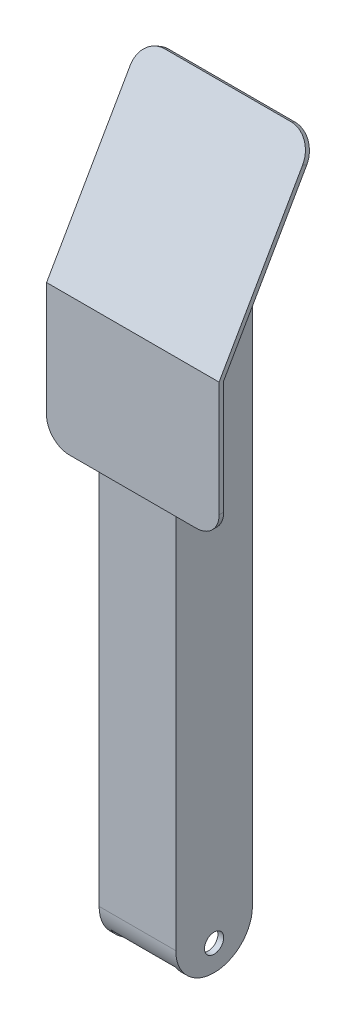
SolidWorks part; units mm, degrees
ref_plane "Front Plane" through (0, 0, 0) normal (0, 0, 1) x (1, 0, 0)
ref_plane "Top Plane" through (0, 0, 0) normal (0, 1, 0) x (1, 0, 0)
ref_plane "Right Plane" through (0, 0, 0) normal (1, 0, 0) x (0, 0, -1)
sketch "Sketch1" plane through (0, 0, 0) normal (0, 1, 0) x (1, 0, 0)
  line L1 (-10.795, -10.795) -> (10.795, -10.795)
  line L2 (-10.795, -10.795) -> (-10.795, 10.795)
  line L3 (-10.795, 10.795) -> (10.795, 10.795)
  line L4 (10.795, -10.795) -> (10.795, 10.795)
  line L5 (-10.795, -10.795) -> (10.795, 10.795) construction
  line L6 (-10.795, 10.795) -> (10.795, -10.795) construction
  line L7 (-12.7, -12.7) -> (12.7, -12.7)
  line L8 (-12.7, -12.7) -> (-12.7, 12.7)
  line L9 (-12.7, 12.7) -> (12.7, 12.7)
  line L10 (12.7, -12.7) -> (12.7, 12.7)
  line L11 (-12.7, -12.7) -> (12.7, 12.7) construction
  line L12 (-12.7, 12.7) -> (12.7, -12.7) construction
  point P0 (0, 0)
  point P6 (0, 0)
  dimension "D1" = 1.905
  dimension "D2" = 25.4
extrude "Boss-Extrude1" add sketch "Sketch1" along normal blind 228.6
sketch "Sketch2" plane through (0, 0, 0) normal (1, 0, 0) x (0, 0, -1)
  line L0 (-12.7, 228.6) -> (-12.7, 0) construction
  line L1 (0, 0) -> (-12.7, 0)
  line L2 (-12.7, 0) -> (-12.7, 12.7)
  line L4 (12.7, 12.7) -> (12.7, 0)
  line L5 (12.7, 0) -> (0, 0)
  line L6 (12.7, 228.6) -> (-12.7, 228.6)
  line L7 (-12.7, 228.6) -> (-12.7, 184.15)
  line L8 (-12.7, 184.15) -> (12.7, 228.6)
  arc A0 (-12.7, 12.7) -> (12.7, 12.7) centre (0, 12.7) ccw
  circle A2 centre (0, 8.509) radius 3.175
  point P17 (0, 0)
  dimension "D2" = 6.35
  dimension "D1" = 44.45
  dimension "D3" = 4.191
extrude "Cut-Extrude1" cut sketch "Sketch2" against normal through all both and the other way through all contours L7 L8 L6 | A0 L2 L1 | A0 L5 L4 | A2
sketch "Sketch3" plane through (0, 0, 0) normal (1, 0, 0) x (0, 0, -1)
  line L0 (-12.7, 184.15) -> (18.604, 238.932)
  line L1 (18.604, 238.932) -> (17.2808, 239.6882)
  line L2 (17.2808, 239.6882) -> (-14.224, 184.5547)
  line L3 (-12.7, 184.15) -> (12.7, 228.6) construction
  line L4 (-12.7, 184.15) -> (-12.7, 138.8347)
  line L5 (-12.7, 184.15) -> (-12.7, 12.7) construction
  line L6 (-12.7, 138.8347) -> (-14.224, 138.8347)
  line L7 (-14.224, 138.8347) -> (-14.224, 184.5547)
  dimension "D1" = 1.524
  dimension "D2" = 63.5
  dimension "D3" = 45.72
extrude "Boss-Extrude2" add sketch "Sketch3" along normal mid plane 57.15
fillet "Fillet1" radius 7.62 4 edges at (28.575, 138.8347, 13.462) (-28.575, 138.8347, 13.462) (-28.575, 239.3101, -17.9424) (28.575, 239.3101, -17.9424)
